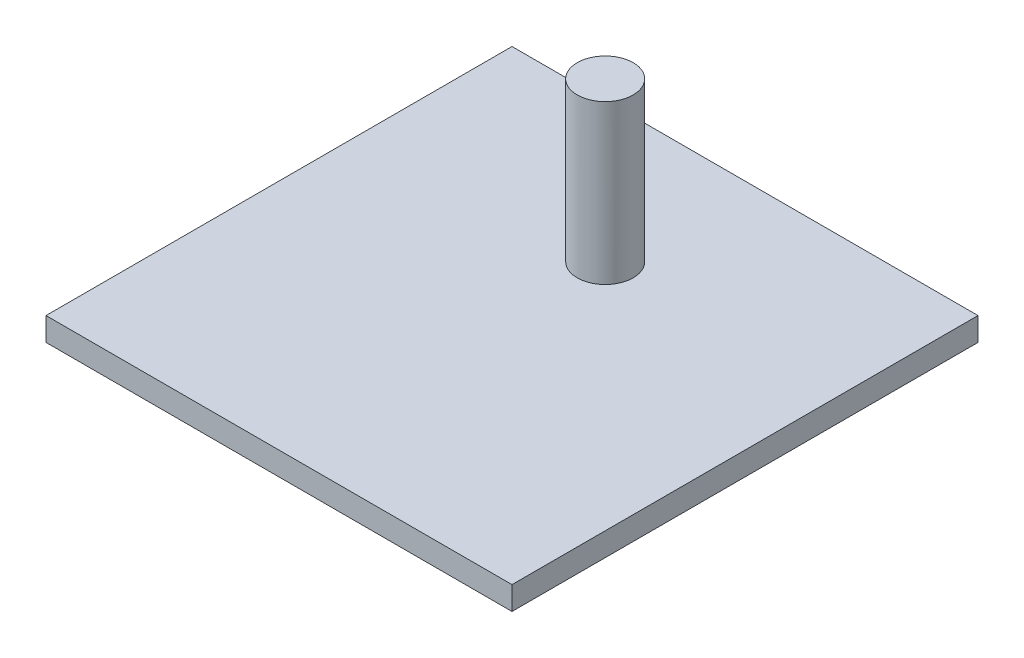
SolidWorks part; units mm, degrees
ref_plane "Front Plane" through (0, 0, 0) normal (0, 0, 1) x (1, 0, 0)
ref_plane "Top Plane" through (0, 0, 0) normal (0, 1, 0) x (1, 0, 0)
ref_plane "Right Plane" through (0, 0, 0) normal (1, 0, 0) x (0, 0, -1)
sketch "Sketch1" plane through (0, 0, 0) normal (0, 1, 0) x (1, 0, 0)
  line L1 (0, 0) -> (200, 0)
  line L2 (0, 0) -> (0, 200)
  line L3 (0, 200) -> (200, 200)
  line L4 (200, 0) -> (200, 200)
  point P5 (-33.6559, 37.8316)
extrude "Boss-Extrude1" add sketch "Sketch1" along normal blind 10
sketch "Sketch2" plane through (0, 10, 0) normal (0, 1, 0) x (-1, 0, 0)
  line L0 (-200, -200) -> (0, -200) construction
  line L1 (0, -200) -> (0, 0) construction
  circle A0 centre (-100, -140) radius 12
  dimension "D2" = 100
  dimension "D3" = 24
  dimension "D1" = 60
extrude "Boss-Extrude2" add sketch "Sketch2" along normal blind 68
